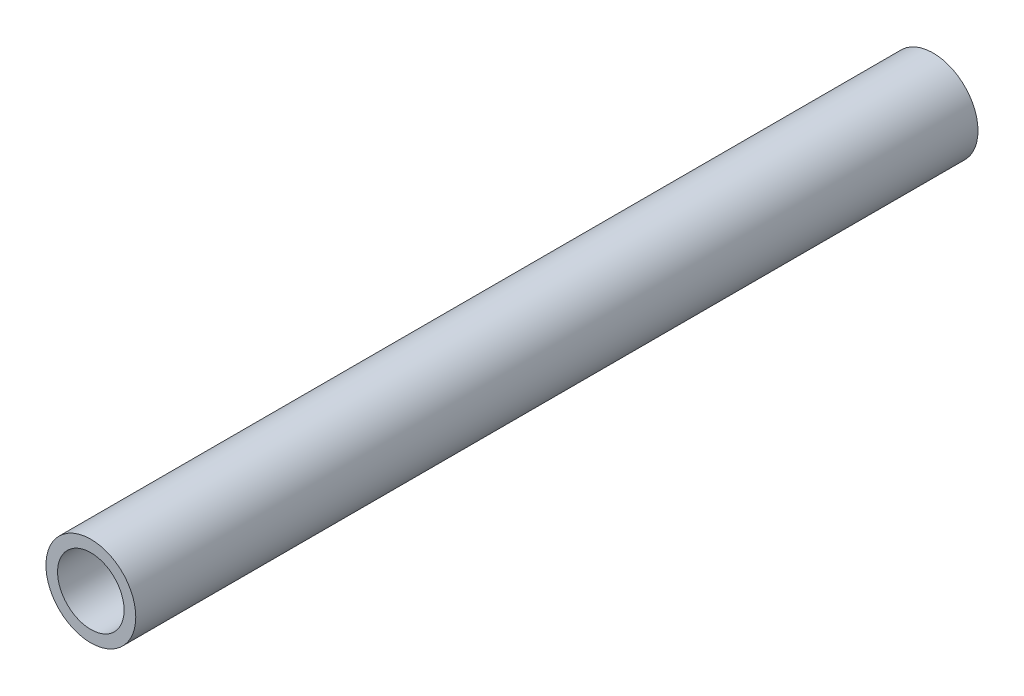
SolidWorks part; units mm, degrees
ref_plane "Front Plane" through (0, 0, 0) normal (0, 0, 1) x (1, 0, 0)
ref_plane "Top Plane" through (0, 0, 0) normal (0, 1, 0) x (1, 0, 0)
ref_plane "Right Plane" through (0, 0, 0) normal (1, 0, 0) x (0, 0, -1)
sketch "Sketch1" plane through (0, 0, 0) normal (0, 0, 1) x (1, 0, 0)
  circle A0 centre (0, 0) radius 10.668
  dimension "Pipe OD" = 21.336
extrude "Extrude-Thin1" add sketch "Sketch1" along normal mid plane 200 thin thin type one direction reverse wall 2.7686
